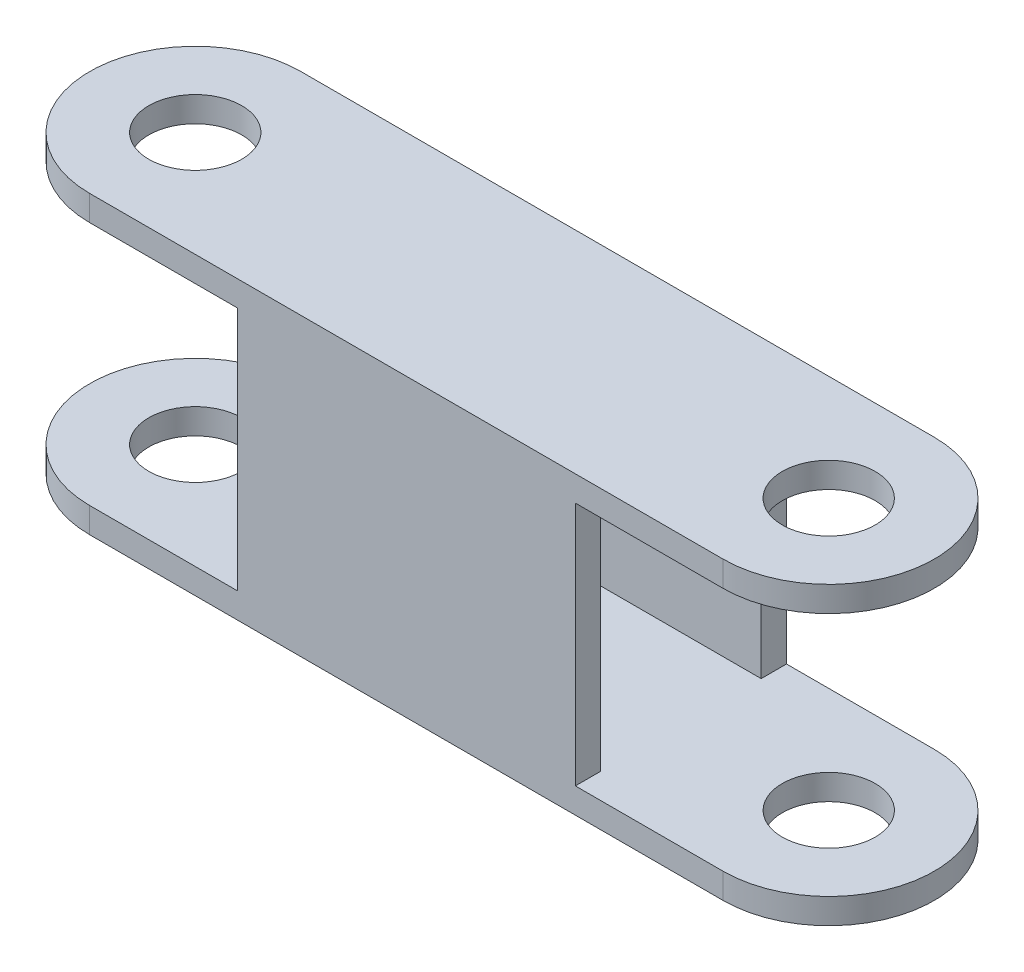
SolidWorks part; units mm, degrees
material "Acrylic (Medium-high impact)"
ref_plane "Front Plane" through (0, 0, 0) normal (0, 0, 1) x (1, 0, 0)
ref_plane "Top Plane" through (0, 0, 0) normal (0, 1, 0) x (1, 0, 0)
ref_plane "Right Plane" through (0, 0, 0) normal (1, 0, 0) x (0, 0, -1)
sketch "Sketch1" plane through (0, 0, 0) normal (0, 1, 0) x (1, 0, 0)
  line L0 (-75, 0) -> (75, 0) construction
  line L1 (-75, 25) -> (75, 25)
  line L2 (-75, -25) -> (75, -25)
  arc A0 (-75, 25) -> (-75, -25) centre (-75, 0) ccw
  arc A1 (75, -25) -> (75, 25) centre (75, 0) ccw
  circle A2 centre (75, 0) radius 11
  circle A3 centre (-75, 0) radius 11
  point P2 (0, 0)
  dimension "D2" = 22
  dimension "D1" = 150
  dimension "D3" = 50
extrude "Boss-Extrude1" add sketch "Sketch1" along normal mid plane 70
sketch "Sketch2" plane through (0, 0, 0) normal (0, 0, 1) x (1, 0, 0)
  line L0 (-100, 0) -> (100, 0) construction
  line L1 (-75, 35) -> (75, 35) construction
  line L2 (-100, 35) -> (-100, -35) construction
  line L3 (100, -35) -> (100, 35) construction
  line L4 (100, 29) -> (40, 29)
  line L5 (40, 29) -> (40, -29)
  line L6 (40, -29) -> (100, -29)
  line L7 (100, -29) -> (100, 29)
  dimension "D1" = 6
  dimension "D2" = 60
extrude "Cut-Extrude1" cut sketch "Sketch2" against normal through all both and the other way through all
mirror "Mirror1" about plane through (0, 0, 0) normal (1, 0, 0) of "Cut-Extrude1"
sketch "Sketch3" plane through (40, 0, 0) normal (1, 0, 0) x (0, 0, -1)
  line L0 (25, -29) -> (-25, -29) construction
  line L1 (-19, 29) -> (19, 29)
  line L2 (-19, 29) -> (-19, -29)
  line L3 (-19, -29) -> (19, -29)
  line L4 (19, 29) -> (19, -29)
  line L5 (-19, 29) -> (19, -29) construction
  line L6 (-19, -29) -> (19, 29) construction
  line L7 (25, 29) -> (25, -29) construction
  point P0 (0, 0)
  dimension "D1" = 6
extrude "Cut-Extrude2" cut sketch "Sketch3" against normal up to next
